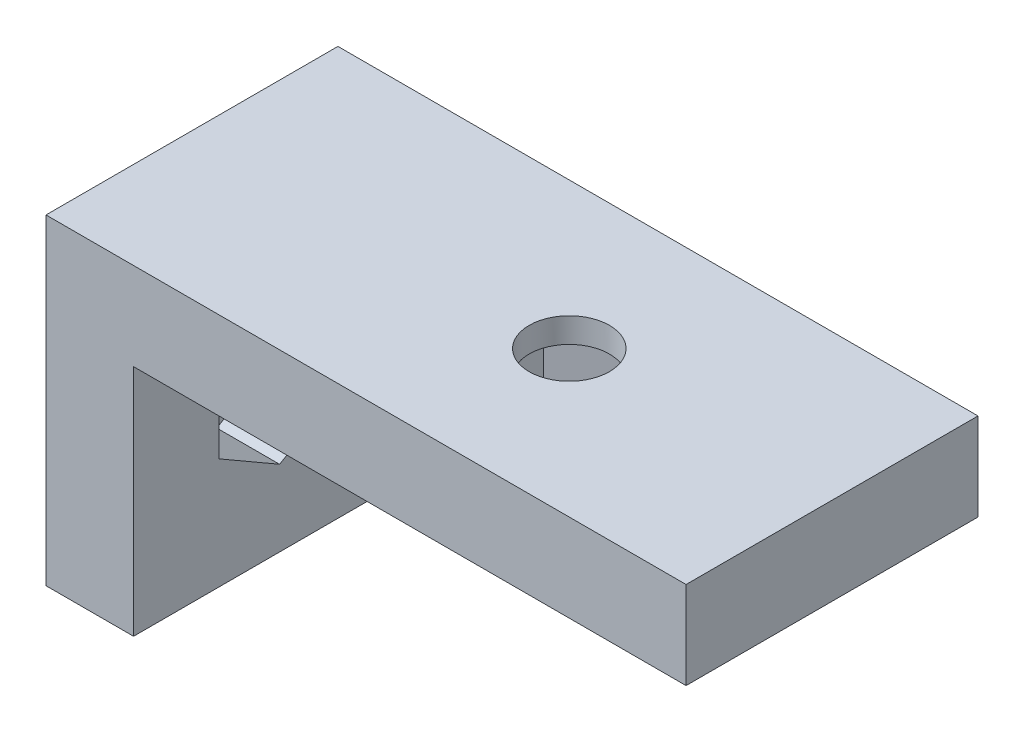
SolidWorks part; units mm, degrees
ref_plane "Спереди" through (0, 0, 0) normal (0, 0, 1) x (1, 0, 0)
ref_plane "Сверху" through (0, 0, 0) normal (0, 1, 0) x (1, 0, 0)
ref_plane "Справа" through (0, 0, 0) normal (1, 0, 0) x (0, 0, -1)
other "Configuration Table"
sketch "Профиль_скобы_6мм" plane through (0, 0, 0) normal (0, 0, 1) x (1, 0, 0)
  line L0 (6.15, -22) -> (12.15, -22)
  line L1 (12.15, -22) -> (12.15, -6)
  line L2 (12.15, -6) -> (50, -6)
  line L3 (50, -6) -> (50, 0)
  line L4 (50, 0) -> (6.15, 0)
  line L5 (6.15, 0) -> (6.15, -22)
  dimension "X001" = 6.15
  dimension "X002" = 12.15
  dimension "X003" = 50
  dimension "Y001" = 22
  dimension "Y002" = 6
extrude "Печатный_корпус_20мм" add sketch "Профиль_скобы_6мм" along normal blind 20
sketch "Винты_полки_М5_эскиз" plane through (0, 0, 0) normal (0, 1, 0) x (1, 0, 0)
  circle A0 centre (32, -10) radius 2.75
  dimension "Диаметр001" = 5.5
  dimension "X001" = 32
  dimension "Y001" = 10
extrude "Винты_полки_М5" cut sketch "Винты_полки_М5_эскиз" against normal through all and the other way through all
sketch "Гайки_полки_М5_эскиз" plane through (0, -6, 0) normal (0, -1, 0) x (1, 0, 0)
  line L0 (32, 14.792) -> (36.15, 12.396)
  line L1 (36.15, 12.396) -> (36.15, 7.604)
  line L2 (36.15, 7.604) -> (32, 5.208)
  line L3 (32, 5.208) -> (27.85, 7.604)
  line L4 (27.85, 7.604) -> (27.85, 12.396)
  line L5 (27.85, 12.396) -> (32, 14.792)
  dimension "X001" = 27.85
  dimension "X002" = 32
  dimension "X003" = 36.15
  dimension "Y001" = 5.208
  dimension "Y002" = 7.604
  dimension "Y003" = 12.396
  dimension "Y004" = 14.792
extrude "Гайки_полки_М5_4_3мм" cut sketch "Гайки_полки_М5_эскиз" against normal blind 4.3
sketch "Винт_рамки_М5_эскиз" plane through (0, 0, 0) normal (1, 0, 0) x (0, 0, -1)
  circle A0 centre (-10, -12) radius 2.75
  dimension "Диаметр001" = 5.5
  dimension "X001" = 10
  dimension "Y001" = 12
extrude "Винт_рамки_М5" cut sketch "Винт_рамки_М5_эскиз" against normal through all and the other way through all
sketch "Гайка_рамки_М5_эскиз" plane through (12.15, 0, 0) normal (1, 0, 0) x (0, 0, -1)
  line L0 (-10, -7.208) -> (-14.15, -9.604)
  line L1 (-14.15, -9.604) -> (-14.15, -14.396)
  line L2 (-14.15, -14.396) -> (-10, -16.792)
  line L3 (-10, -16.792) -> (-5.85, -14.396)
  line L4 (-5.85, -14.396) -> (-5.85, -9.604)
  line L5 (-5.85, -9.604) -> (-10, -7.208)
  dimension "X001" = 14.15
  dimension "X002" = 10
  dimension "X003" = 5.85
  dimension "Y001" = 16.792
  dimension "Y002" = 14.396
  dimension "Y003" = 9.604
  dimension "Y004" = 7.208
extrude "Гайка_рамки_М5_4_3мм" cut sketch "Гайка_рамки_М5_эскиз" against normal blind 4.3
